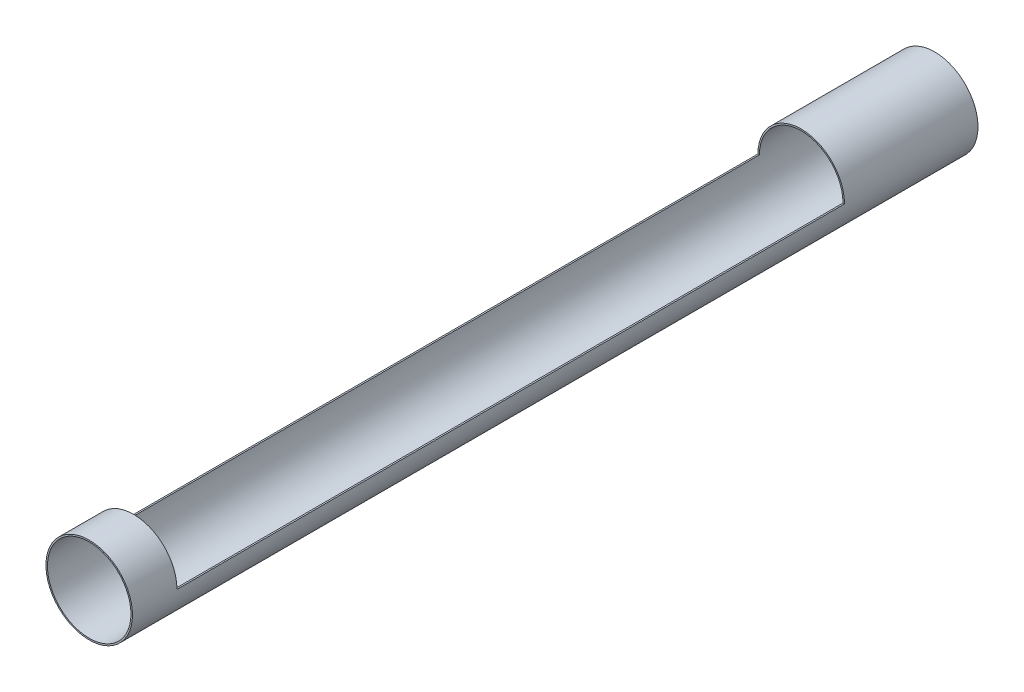
SolidWorks part; units mm, degrees
ref_plane "Front Plane" through (0, 0, 0) normal (0, 0, 1) x (1, 0, 0)
ref_plane "Top Plane" through (0, 0, 0) normal (0, 1, 0) x (1, 0, 0)
ref_plane "Right Plane" through (0, 0, 0) normal (1, 0, 0) x (0, 0, -1)
sketch "Sketch1" plane through (0, 0, 0) normal (0, 0, 1) x (1, 0, 0)
  circle A0 centre (0, 0) radius 49.403
  circle A1 centre (0, 0) radius 47.6885
  dimension "D1" = 98.806
  dimension "D2" = 95.377
extrude "Boss-Extrude1" add sketch "Sketch1" along normal blind 152.4
sketch "Sketch2" plane through (0, 0, 152.4) normal (0, 0, 1) x (1, 0, 0)
  line L0 (-49.403, 0) -> (-47.6885, 0)
  line L1 (47.6885, 0) -> (49.403, 0)
  arc A0 (-49.403, 0) -> (49.403, 0) centre (0, 0) ccw
  arc A1 (-47.6885, 0) -> (47.6885, 0) centre (0, 0) ccw
extrude "Boss-Extrude2" add sketch "Sketch2" along normal blind 762
sketch "Sketch3" plane through (0, 0, 914.4) normal (0, 0, 1) x (1, 0, 0)
  circle A0 centre (0, 0) radius 49.403
  circle A1 centre (0, 0) radius 47.6885
extrude "Boss-Extrude3" add sketch "Sketch3" along normal blind 50.8
